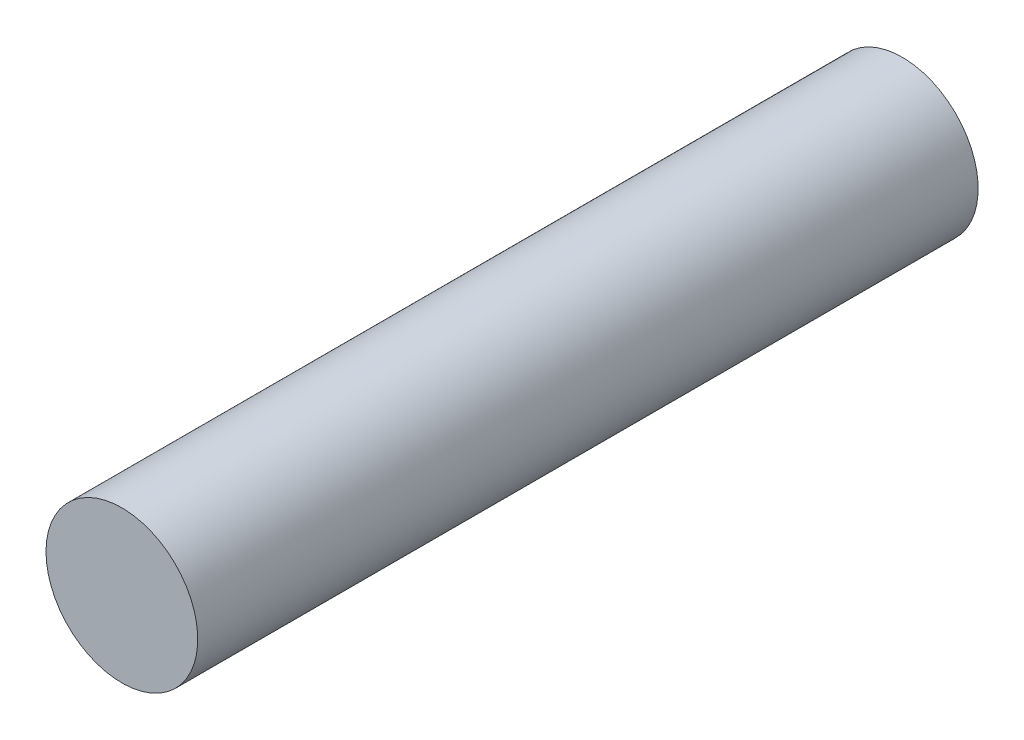
SolidWorks part; units mm, degrees
ref_plane "Front Plane" through (0, 0, 0) normal (0, 0, 1) x (1, 0, 0)
ref_plane "Top Plane" through (0, 0, 0) normal (0, 1, 0) x (1, 0, 0)
ref_plane "Right Plane" through (0, 0, 0) normal (1, 0, 0) x (0, 0, -1)
sketch "Sketch1" plane through (0, 0, 0) normal (0, 0, 1) x (1, 0, 0)
  circle A0 centre (0, 0) radius 17.5
  dimension "D1" = 35
extrude "Boss-Extrude1" add sketch "Sketch1" along normal blind 180
